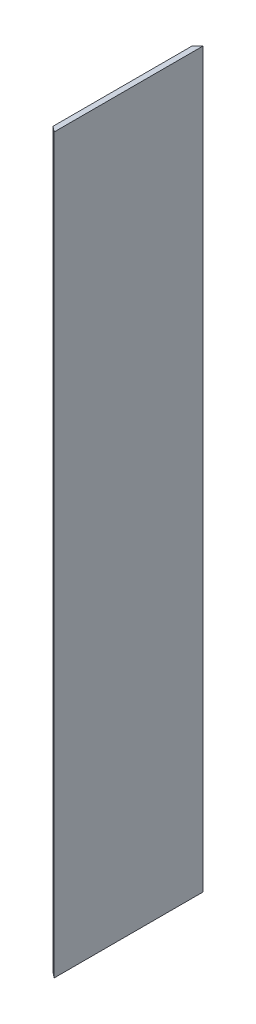
SolidWorks part; units mm, degrees
ref_plane "Спереди" through (0, 0, 0) normal (0, 0, 1) x (1, 0, 0)
ref_plane "Сверху" through (0, 0, 0) normal (0, 1, 0) x (1, 0, 0)
ref_plane "Справа" through (0, 0, 0) normal (1, 0, 0) x (0, 0, -1)
sketch "Эскиз1" plane through (0, 0, 0) normal (0, 1, 0) x (1, 0, 0)
  line L0 (1.0264, -3.4818) -> (1.0264, -104.6416)
  line L1 (1.0264, -104.6416) -> (5.0264, -107.8388)
  line L2 (5.0264, -107.8388) -> (5.0264, 0.4912)
  line L3 (5.0264, 0.4912) -> (1.0264, -3.4818)
  dimension "D1" = 4
extrude "Вытянуть1" add sketch "Эскиз1" along normal blind 533
